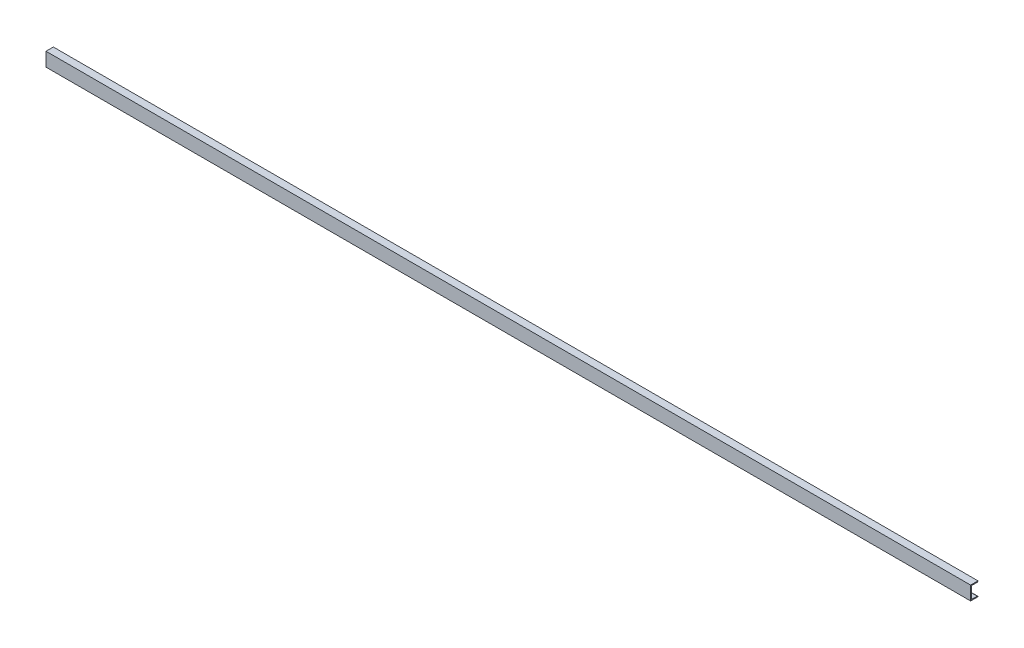
SolidWorks part; units mm, degrees
ref_plane "Front Plane" through (0, 0, 0) normal (0, 0, 1) x (1, 0, 0)
ref_plane "Top Plane" through (0, 0, 0) normal (0, 1, 0) x (1, 0, 0)
ref_plane "Right Plane" through (0, 0, 0) normal (1, 0, 0) x (0, 0, -1)
sketch "Sketch1" plane through (0, 0, 0) normal (1, 0, 0) x (0, 0, -1)
  line L0 (0, 0) -> (40, 0)
  line L1 (35, 5) -> (5, 5)
  line L2 (5, 5) -> (5, 70)
  line L3 (5, 70) -> (35, 70)
  line L4 (40, 75) -> (0, 75)
  line L5 (0, 75) -> (0, 0)
  arc A0 (40, 0) -> (35, 5) centre (35, 0) ccw
  arc A1 (35, 70) -> (40, 75) centre (35, 75) ccw
  dimension "D1" = 75
  dimension "D2" = 40
  dimension "D3" = 5
  dimension "D4" = 5
  dimension "D5" = 5
extrude "Boss-Extrude1" add sketch "Sketch1" along normal blind 5030
equation "\"channelSteel_length\"=5030.0"
equation "\"D1@Boss-Extrude1\"=\"channelSteel_length\""
equation "\"SquareTube_length\"=1923.0"
equation "\"SquareTube_wheel_length\"= 750"
equation "\"SquareTube_inFront1_cutDepth50_R\"=0.5"
equation "\"SquareTube_inFront1_cutDepth50_L\"=0.5"
equation "\"SquareTube_inBack1_cutDepth50_R\"=50"
equation "\"SquareTube_inBack1_cutDepth50_L\"=50"
equation "\"CarBeamWidth\"=700.0"
equation "\"MetalSheet_3mm_length\"=5030.0"
equation "\"MetalSheet_3mm_width\"=1923.0"
equation "\"MetalSheet_3mm_FloorCut_L_length\"=1764.0"
equation "\"MetalSheet_3mm_FloorCut_L_disdance\"=1665.0"
equation "\"MetalSheet_3mm_FloorCut_R_length\"=1764.0"
equation "\"MetalSheet_3mm_FloorCut_R_disdance\"=1665.0"
equation "\"indoorHeight\"=1940.0"
equation "\"x\"=66.0"
equation "\"da\"=62.0"
equation "\"SquareTube_inFront2_cutDepth50_R\"=0.5"
equation "\"SquareTube_inFront2_cutDepth50_L\"=0.5"
equation "\"SquareTube_inFront3_cutDepth50_R\"=0.5"
equation "\"SquareTube_inFront3_cutDepth50_L\"=0.5"
equation "\"SquareTube_inFront4_cutDepth50_R\"=0.5"
equation "\"SquareTube_inFront4_cutDepth50_L\"=0.5"
equation "\"SquareTube_inFront5_cutDepth50_R\"=50"
equation "\"SquareTube_inFront5_cutDepth50_L\"=50"
equation "\"SquareTube_inFront6_cutDepth50_R\"=50"
equation "\"SquareTube_inFront6_cutDepth50_L\"=50"
equation "\"SquareTube_inFront7_cutDepth50_R\"=50"
equation "\"SquareTube_inFront7_cutDepth50_L\"=50"
equation "\"SquareTube_inFront8_cutDepth50_R\"=50"
equation "\"SquareTube_inFront8_cutDepth50_L\"=50"
equation "\"SquareTube_inFront9_cutDepth50_R\"=50"
equation "\"SquareTube_inFront9_cutDepth50_L\"=50"
equation "\"SquareTube_inFront10_cutDepth50_R\"=50"
equation "\"SquareTube_inFront10_cutDepth50_L\"=50"
equation "\"SquareTube_inBack2_cutDepth50_R\"=50"
equation "\"SquareTube_inBack2_cutDepth50_L\"=50"
equation "\"SquareTube_inBack3_cutDepth50_R\"=50"
equation "\"SquareTube_inBack3_cutDepth50_L\"=50"
equation "\"SquareTube_inBack4_cutDepth50_R\"=50"
equation "\"SquareTube_inBack4_cutDepth50_L\"=50"
equation "\"SquareTube_inBack5_cutDepth50_R\"=50"
equation "\"SquareTube_inBack5_cutDepth50_L\"=50"
equation "\"SquareTube_inBack6_cutDepth50_R\"=0.5"
equation "\"SquareTube_inBack6_cutDepth50_L\"=0.5"
